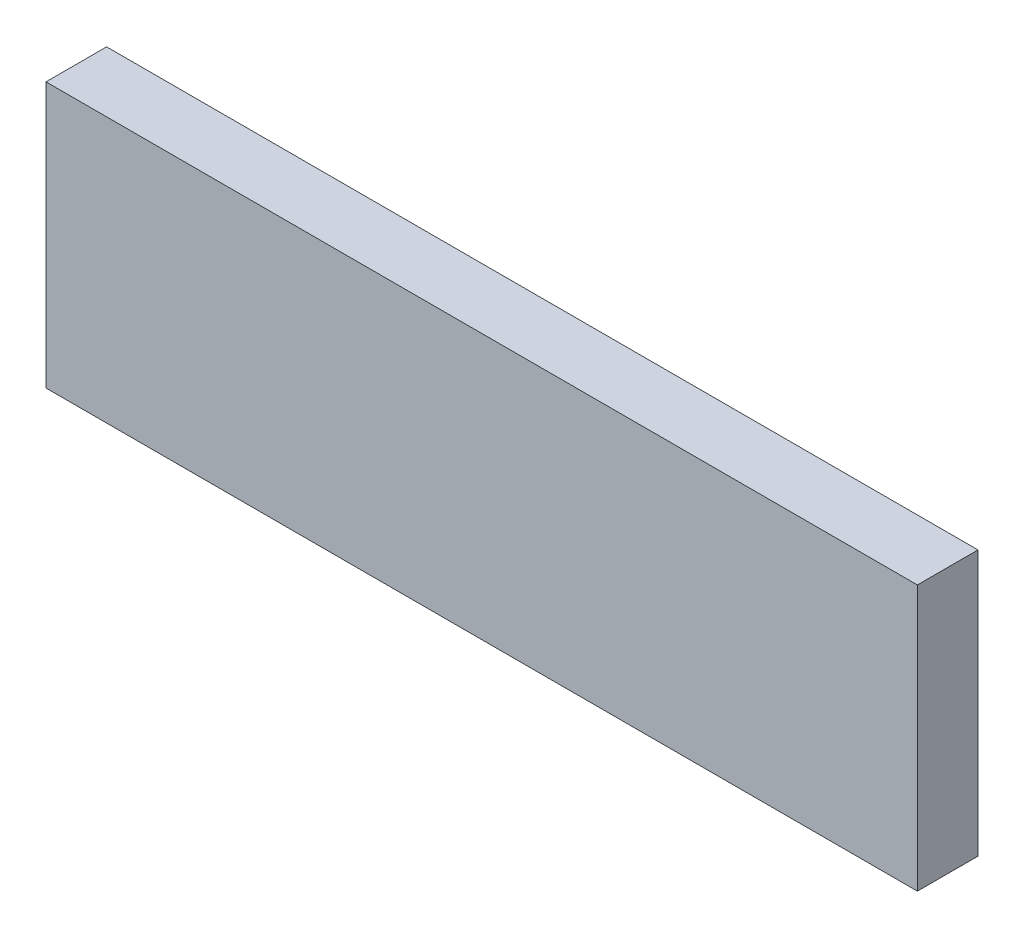
SolidWorks part; units mm, degrees
ref_plane "前视" through (0, 0, 0) normal (0, 0, 1) x (1, 0, 0)
ref_plane "上视" through (0, 0, 0) normal (0, 1, 0) x (1, 0, 0)
ref_plane "右视" through (0, 0, 0) normal (1, 0, 0) x (0, 0, -1)
sketch "草图1" plane through (0, 0, 0) normal (0, 0, 1) x (1, 0, 0)
  line L1 (-115, 35) -> (115, 35)
  line L2 (-115, 35) -> (-115, -35)
  line L3 (-115, -35) -> (115, -35)
  line L4 (115, 35) -> (115, -35)
  line L5 (0, 76.4471) -> (0, -77.2872) construction
  dimension "D1" = 70
  dimension "D2" = 230
  dimension "D4" = 115
extrude "基体-拉伸" add sketch "草图1" along normal blind 16
